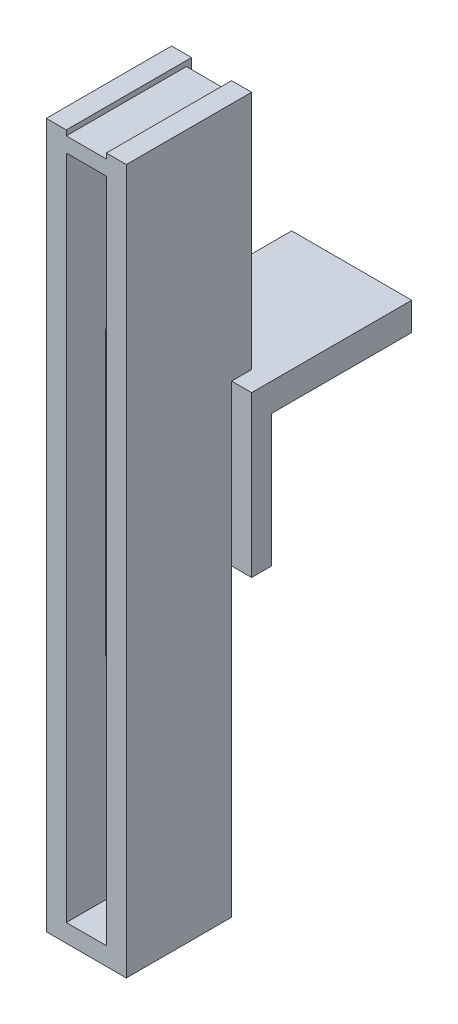
SolidWorks part; units mm, degrees
ref_plane "Front Plane" through (0, 0, 0) normal (0, 0, 1) x (1, 0, 0)
ref_plane "Top Plane" through (0, 0, 0) normal (0, 1, 0) x (1, 0, 0)
ref_plane "Right Plane" through (0, 0, 0) normal (1, 0, 0) x (0, 0, -1)
sketch "Sketch2" plane through (0, 0, 0) normal (1, 0, 0) x (0, 0, -1)
  line L0 (0, 0) -> (0, -40)
  line L3 (0, -40) -> (5, -40)
  line L4 (5, -40) -> (5, -7)
  line L5 (5, -7) -> (40, -7)
  line L6 (40, -7) -> (40, 0)
  line L7 (40, 0) -> (0, 0)
  dimension "D1" = 33
  dimension "D2" = 7
  dimension "D3" = 35
  dimension "D4" = 5
extrude "Boss-Extrude2" add sketch "Sketch2" along normal mid plane 30
sketch "Sketch3" plane through (0, 0, 0) normal (1, 0, 0) x (0, 0, -1)
  line L0 (0, -116) -> (-8.5, -116)
  line L1 (5, -7) -> (40, -7) construction
  line L2 (0, -116) -> (0, 40.464)
  line L3 (0, 40.464) -> (-16.5323, 11.8292)
  line L4 (-16.5323, 11.8292) -> (-16.5323, -58.6123)
  line L5 (-16.5323, -58.6123) -> (-8.5, -71.6269)
  line L6 (-8.5, -71.6269) -> (-8.5, -116)
  point P2 (0, 0)
  point P5 (0, 0)
  dimension "D1" = 109
  dimension "D2" = 8.5
  dimension "90" = 30
extrude "Boss-Extrude3" add sketch "Sketch3" along normal mid plane 10
sketch "Sketch4" plane through (-5, 0, 0) normal (-1, 0, 0) x (0, 0, 1)
  line L1 (0, 60) -> (26.3, 60)
  line L2 (26.3, 60) -> (26.3, -116)
  line L3 (26.3, -116) -> (0, -116)
  line L6 (0, -116) -> (0, 0)
  line L7 (0, 0) -> (-5, 0)
  line L8 (-40, 0) -> (0, 0) construction
  line L9 (-5, 0) -> (-5, 60)
  line L10 (-5, 60) -> (0, 60)
  dimension "D1" = 5
  dimension "D2" = 60
  dimension "D3" = 176
extrude "Boss-Extrude4" add sketch "Sketch4" along normal blind 5 contours L3 L6 L7 L9 L10 L1 L2
mirror "Mirror1" about plane through (0, 0, 0) normal (1, 0, 0) of "Boss-Extrude4"
sketch "Sketch8" plane through (5, 0, 0) normal (-1, 0, 0) x (0, 0, 1)
  line L0 (0, 0) -> (0, 55)
  line L1 (0, 55) -> (26.3, 55)
  line L2 (26.3, 60) -> (26.3, -116) construction
  line L3 (26.3, 55) -> (26.3, 58.7)
  line L4 (26.3, 58.7) -> (-3.7, 58.7)
  line L5 (-3.7, 58.7) -> (-3.7, 0)
  line L6 (0, 0) -> (-5, 0) construction
  line L7 (-3.7, 0) -> (0, 0)
  point P14 (-2.5, 0)
  dimension "D1" = 30
  dimension "D2" = 3.7
  dimension "D3" = 55
extrude "Boss-Extrude5" add sketch "Sketch8" along normal blind 10
sketch "Sketch9" plane through (0, 0, 8.5) normal (0, 0, 1) x (1, 0, 0)
  line L0 (5, 55) -> (5, -116) construction
  line L1 (-5, -116) -> (5, -116)
  line L2 (-5, -116) -> (-5, -111.5)
  line L3 (-5, -111.5) -> (5, -111.5)
  line L4 (5, -116) -> (5, -111.5)
  dimension "D1" = 4.5
extrude "Boss-Extrude6" add sketch "Sketch9" along normal blind 17.8
